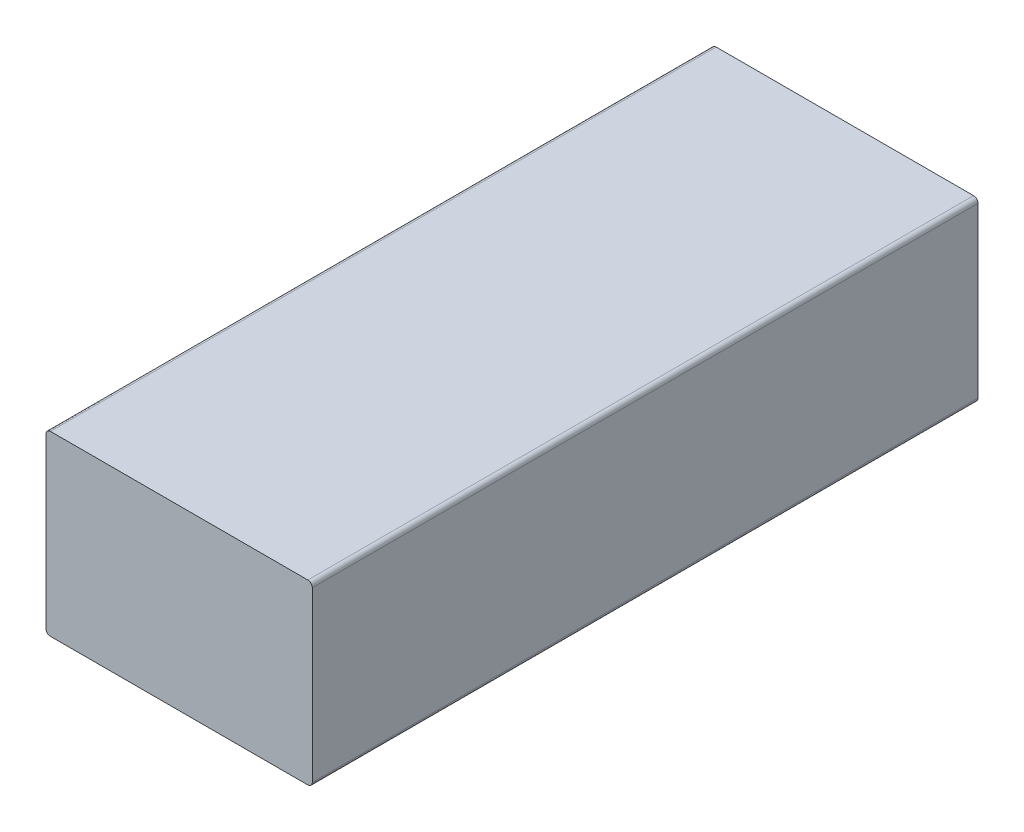
SolidWorks part; units mm, degrees
material "炭素鋼(普通)"
ref_plane "正面" through (0, 0, 0) normal (0, 0, 1) x (1, 0, 0)
ref_plane "平面" through (0, 0, 0) normal (0, 1, 0) x (1, 0, 0)
ref_plane "右側面" through (0, 0, 0) normal (1, 0, 0) x (0, 0, -1)
sketch "ｽｹｯﾁ1" plane through (0, 0, 0) normal (0, 0, 1) x (1, 0, 0)
  line L1 (-3, -2) -> (3, -2)
  line L2 (-3, -2) -> (-3, 2)
  line L3 (-3, 2) -> (3, 2)
  line L4 (3, -2) -> (3, 2)
  line L5 (-3, -2) -> (3, 2) construction
  line L6 (-3, 2) -> (3, -2) construction
  point P0 (0, 0)
  dimension "D1" = 6
  dimension "D2" = 4
extrude "ﾎﾞｽ - 押し出し1" add sketch "ｽｹｯﾁ1" along normal blind 15
fillet "ﾌｨﾚｯﾄ1" radius 0.1 4 edges at (-3, -2, 7.5) (3, -2, 7.5) (-3, 2, 7.5) (3, 2, 7.5)
